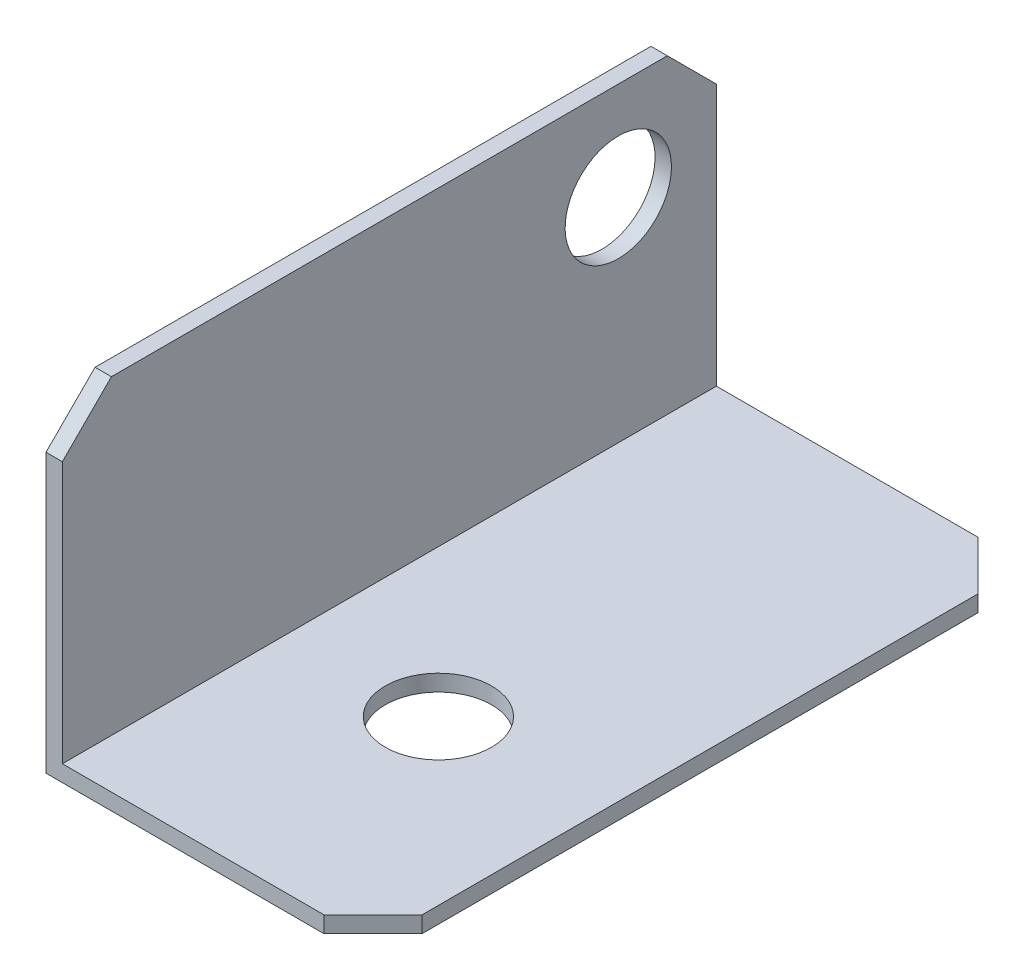
SolidWorks part; units mm, degrees
material "Alu"
ref_plane "Ebene vorne" through (0, 0, 0) normal (0, 0, 1) x (1, 0, 0)
ref_plane "Ebene oben" through (0, 0, 0) normal (0, 1, 0) x (1, 0, 0)
ref_plane "Ebene rechts" through (0, 0, 0) normal (1, 0, 0) x (0, 0, -1)
sketch "Skizze1" plane through (0, 0, 0) normal (0, 0, 1) x (1, 0, 0)
  line L0 (0, 20) -> (0, 0)
  line L1 (0, 0) -> (20, 0)
  dimension "D1" = 20
extrude "Linear-Austragen-Dünn1" add sketch "Skizze1" along normal mid plane 40 thin thin type one direction reverse wall 1
chamfer "Fase1" distance 3 angle 45 4 edges at (20, 0.5, 20) (20, 0.5, -20) (0.5, 20, -20) (0.5, 20, 20)
sketch "Skizze2" plane through (0, 1, 0) normal (0, 1, 0) x (1, 0, 0)
  line L0 (1, -20) -> (17, -20) construction
  line L1 (20, -17) -> (20, 17) construction
  circle A0 centre (10, -6) radius 3.25
  dimension "D1" = 6.5
  dimension "D2" = 14
  dimension "D3" = 10
extrude "Schnitt-Linear austragen1" cut sketch "Skizze2" against normal blind 10
sketch "Skizze3" plane through (1, 0, 0) normal (1, 0, 0) x (0, 0, -1)
  line L0 (-17, 20) -> (17, 20) construction
  line L1 (20, 17) -> (20, 1) construction
  circle A0 centre (14, 14) radius 3.25
  dimension "D1" = 6.5
  dimension "D3" = 6
  dimension "D2" = 6
extrude "Schnitt-Linear austragen2" cut sketch "Skizze3" against normal blind 10
